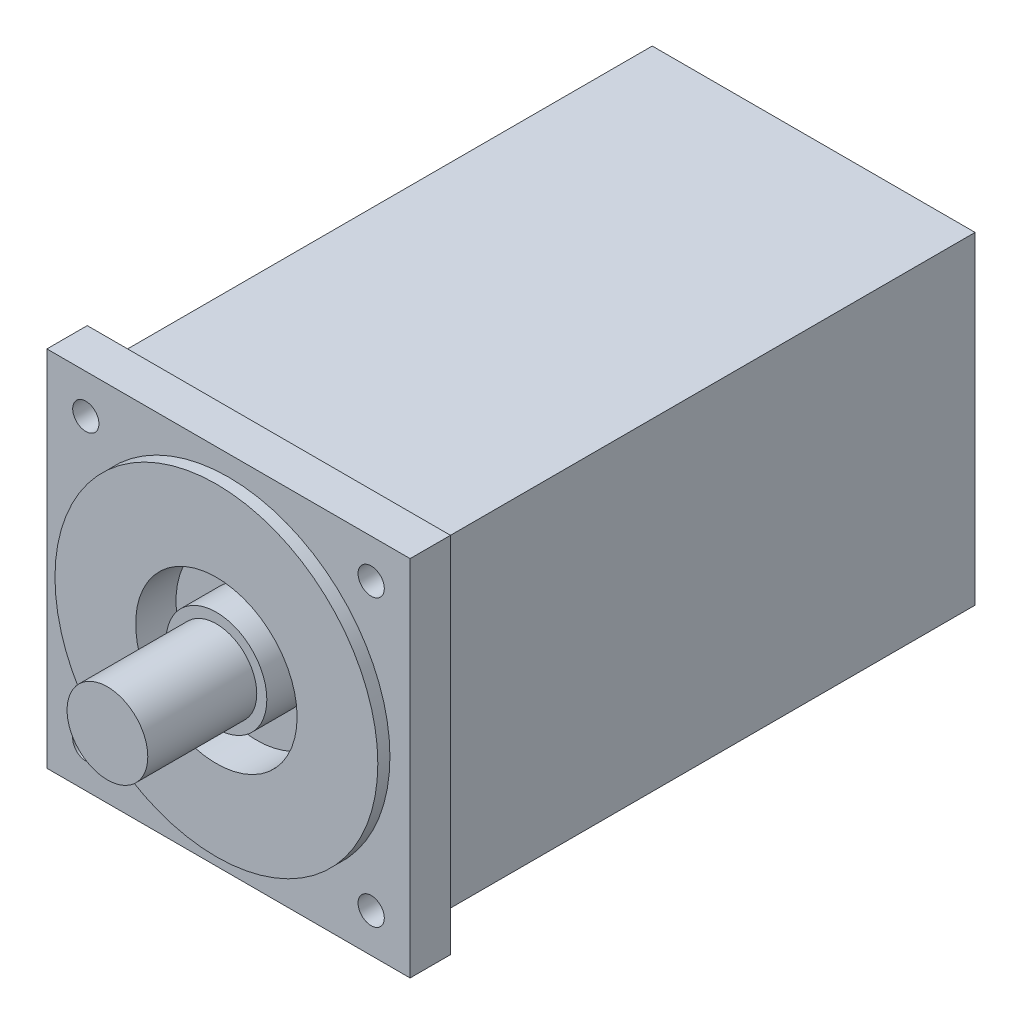
SolidWorks part; units mm, degrees
ref_plane "前视基准面" through (0, 0, 0) normal (0, 0, 1) x (1, 0, 0)
ref_plane "上视基准面" through (0, 0, 0) normal (0, 1, 0) x (1, 0, 0)
ref_plane "右视基准面" through (0, 0, 0) normal (1, 0, 0) x (0, 0, -1)
sketch "草图1" plane through (0, 0, 0) normal (0, 0, 1) x (1, 0, 0)
  line L1 (0, 0) -> (80, 0)
  line L2 (0, 0) -> (0, -80)
  line L3 (0, -80) -> (80, -80)
  line L4 (80, 0) -> (80, -80)
  dimension "D1" = 80
  dimension "D2" = 80
extrude "拉伸1" add sketch "草图1" along normal blind 134
sketch "草图2" plane through (0, 0, 134) normal (0, 0, 1) x (1, 0, 0)
  circle A0 centre (40, -40) radius 40
extrude "拉伸2" add sketch "草图2" along normal blind 1
sketch "草图3" plane through (0, 0, 135) normal (0, 0, 1) x (1, 0, 0)
  line L1 (-5, 5) -> (85, 5)
  line L2 (-5, 5) -> (-5, -85)
  line L3 (-5, -85) -> (85, -85)
  line L4 (85, 5) -> (85, -85)
  arc A0 (40, 0) -> (0, -40) centre (40, -40) ccw construction
  circle A1 centre (40, -40) radius 40 construction
  dimension "D1" = 45
  dimension "D2" = 45
  dimension "D3" = 90
  dimension "D4" = 90
extrude "拉伸3" add sketch "草图3" along normal blind 10
sketch "草图4" plane through (0, 0, 145) normal (0, 0, 1) x (1, 0, 0)
  circle A0 centre (40, -40) radius 40
extrude "拉伸4" add sketch "草图4" along normal blind 3
sketch "草图5" plane through (0, 0, 148) normal (0, 0, 1) x (1, 0, 0)
  circle A0 centre (40, -40) radius 20
  dimension "D1" = 40
extrude "切除-拉伸1" cut sketch "草图5" against normal blind 10
sketch "草图6" plane through (0, 0, 138) normal (0, 0, 1) x (1, 0, 0)
  circle A0 centre (40, -40) radius 12.5
  dimension "D1" = 25
extrude "拉伸5" add sketch "草图6" along normal blind 10
sketch "草图7" plane through (0, 0, 148) normal (0, 0, 1) x (1, 0, 0)
  circle A0 centre (40, -40) radius 10
extrude "拉伸6" add sketch "草图7" along normal blind 27
sketch "草图9" plane through (0, 0, 145) normal (0, 0, 1) x (1, 0, 0)
  circle A1 centre (75.3553, -4.6447) radius 3.25
  circle A2 centre (75.3553, -75.3553) radius 3.25
  circle A3 centre (4.6447, -75.3553) radius 3.25
  circle A4 centre (4.6447, -4.6447) radius 3.25
extrude "切除-拉伸2" cut sketch "草图9" against normal blind 10
